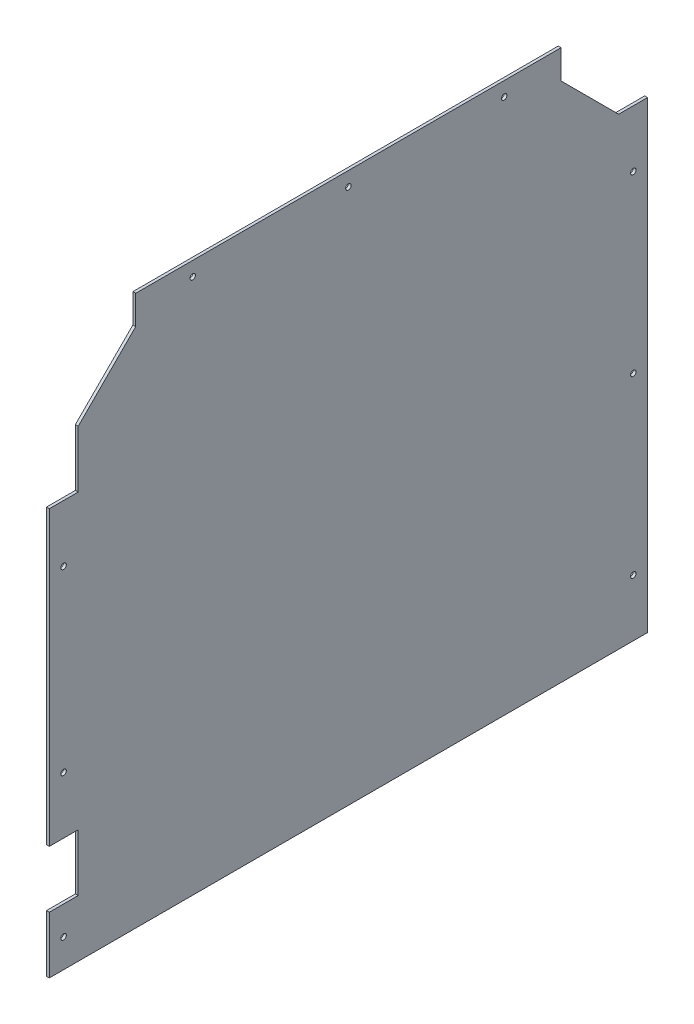
SolidWorks part; units mm, degrees
ref_plane "Front Plane" through (0, 0, 0) normal (0, 0, 1) x (1, 0, 0)
ref_plane "Top Plane" through (0, 0, 0) normal (0, 1, 0) x (1, 0, 0)
ref_plane "Right Plane" through (0, 0, 0) normal (1, 0, 0) x (0, 0, -1)
sketch "Sketch1" plane through (0, 0, 0) normal (1, 0, 0) x (0, 0, -1)
  line L1 (315, -289.5) -> (-315, -289.5)
  line L2 (315, -289.5) -> (315, 289.5)
  line L3 (315, 289.5) -> (-315, 289.5)
  line L4 (-315, -289.5) -> (-315, 289.5)
  line L5 (315, -289.5) -> (-315, 289.5) construction
  line L6 (315, 289.5) -> (-315, -289.5) construction
  point P0 (0, 0)
  dimension "D1" = 630
  dimension "D2" = 579
extrude "Boss-Extrude1" add sketch "Sketch1" along normal mid plane 3
sketch "Sketch2" plane through (-1.5, 0, 0) normal (-1, 0, 0) x (0, 0, 1)
  line L0 (-224, 289.5) -> (-224, 259.0858)
  line L1 (-315, 289.5) -> (315, 289.5) construction
  line L2 (-224, 259.0858) -> (-284.5858, 198.5)
  line L3 (-284.5858, 198.5) -> (-315, 198.5)
  line L4 (-315, -289.5) -> (-315, 289.5) construction
  line L5 (-315, 198.5) -> (-315, 289.5)
  line L6 (-315, 289.5) -> (-224, 289.5)
  line L7 (224, 289.5) -> (224, 259.0858)
  line L8 (224, 259.0858) -> (284.5858, 198.5)
  line L9 (284.5858, 198.5) -> (315, 198.5)
  line L10 (315, 289.5) -> (315, -289.5) construction
  line L11 (315, 198.5) -> (315, 289.5)
  line L12 (315, 289.5) -> (224, 289.5)
  line L13 (-225, 289.5) -> (-225, 259.5) construction
  line L14 (-225, 259.5) -> (-285, 199.5) construction
  line L15 (-285, 199.5) -> (-315, 199.5) construction
  point P20 (-224, 274.2929)
  dimension "D1" = 1
  dimension "D2" = 1
  dimension "D3" = 30
  dimension "D4" = 90
extrude "Cut-Extrude1" cut sketch "Sketch2" against normal through all
sketch "Sketch3" plane through (-1.5, 0, 0) normal (-1, 0, 0) x (0, 0, 1)
  line L0 (315, 198.5) -> (315, -289.5) construction
  line L1 (284.5858, 198.5) -> (315, 198.5)
  line L2 (284.5858, 198.5) -> (284.5858, 138.5)
  line L3 (284.5858, 138.5) -> (315, 138.5)
  line L4 (315, 198.5) -> (315, 138.5)
  line L5 (284.5858, -229.5) -> (284.5858, -289.5) construction
  line L6 (315, -169.5) -> (284.5858, -169.5)
  line L7 (315, -169.5) -> (315, -229.5)
  line L8 (315, -229.5) -> (284.5858, -229.5)
  line L9 (284.5858, -169.5) -> (284.5858, -229.5)
  line L10 (315, -289.5) -> (-315, -289.5) construction
  dimension "D1" = 60
extrude "Cut-Extrude2" cut sketch "Sketch3" against normal through all
hole_wizard "M5 Clearance Hole1" positions "Sketch4" profile "Sketch5" hole size "M5" standard "DIN" end condition through all
sketch "Sketch4" plane through (-1.5, 0, 0) normal (-1, 0, 0) x (0, 0, 1)
  line L0 (-164, 274.5) -> (0, 274.5) construction
  line L1 (0, 274.5) -> (164, 274.5) construction
  line L3 (-300, 138.5) -> (-300, -45.5) construction
  line L4 (-300, -45.5) -> (-300, -229.5) construction
  line L6 (300, 78.5) -> (300, -109.5) construction
  line L7 (300, -109.5) -> (300, -259.5) construction
  line L9 (-315, -289.5) -> (-315, 198.5) construction
  line L10 (-224, 289.5) -> (224, 289.5) construction
  line L11 (-300, -45.5) -> (-315, -45.5) construction
  line L13 (-315, 198.5) -> (-284.5858, 198.5) construction
  line L14 (-224, 259.0858) -> (-224, 289.5) construction
  line L15 (0, 274.5) -> (0, 289.5) construction
  line L17 (315, -15.5) -> (300, -15.5) construction
  line L18 (315, 138.5) -> (315, -169.5) construction
  line L20 (284.5858, 138.5) -> (315, 138.5) construction
  line L21 (315, -259.5) -> (300, -259.5) construction
  line L22 (315, -229.5) -> (315, -289.5) construction
  point P0 (-164, 274.5)
  point P2 (0, 274.5)
  point P4 (164, 274.5)
  point P6 (300, 78.5)
  point P8 (300, -109.5)
  point P10 (300, -259.5)
  point P12 (-300, -229.5)
  point P14 (-300, -45.5)
  point P16 (-300, 138.5)
  dimension "D1" = 15
  dimension "D2" = 15
  dimension "D3" = 60
  dimension "D4" = 60
  dimension "D5" = 15
  dimension "D6" = 60
sketch "Sketch5" plane through (-1.5, 274.5, -164) normal (0, 1, 0) x (0, 0, 1)
  line L0 (0, 0) -> (0, 3)
  line L1 (0, 3) -> (2.9, 3)
  line L2 (2.9, 3) -> (2.9, 0)
  line L5 (2.9, 0) -> (0, 0)
  line L11 (0, -6.35) -> (0, 107.95) construction
  dimension "Thru Hole Dia." = 5.8
  dimension "Thru Hole Depth" = 3
